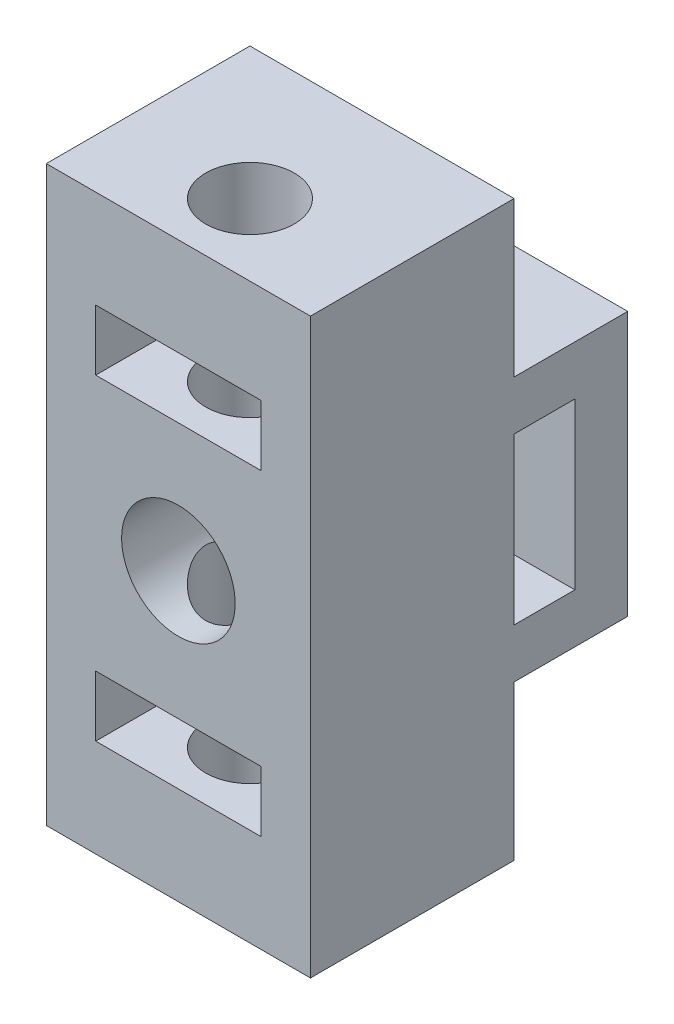
SolidWorks part; units mm, degrees
ref_plane "Front Plane" through (0, 0, 0) normal (0, 0, 1) x (1, 0, 0)
ref_plane "Top Plane" through (0, 0, 0) normal (0, 1, 0) x (1, 0, 0)
ref_plane "Right Plane" through (0, 0, 0) normal (1, 0, 0) x (0, 0, -1)
sketch "Sketch1" plane through (0, 0, 0) normal (0, 1, 0) x (1, 0, 0)
  line L1 (-5, -5) -> (5, -5)
  line L2 (-5, -5) -> (-5, 5)
  line L3 (-5, 5) -> (5, 5)
  line L4 (5, -5) -> (5, 5)
  line L5 (-5, -5) -> (5, 5) construction
  line L6 (-5, 5) -> (5, -5) construction
  point P0 (0, 0)
  dimension "D1" = 10
  dimension "D2" = 10
extrude "Boss-Extrude1" add sketch "Sketch1" along normal blind 5
sketch "Sketch2" plane through (0, 5, 0) normal (0, 1, 0) x (1, 0, 0)
  circle A0 centre (0, 0) radius 1.675
  dimension "D1" = 3.35
extrude "Cut-Extrude1" cut sketch "Sketch2" against normal through all both and the other way through all
sketch "Sketch3" plane through (0, 5, 0) normal (0, 1, 0) x (1, 0, 0)
  line L0 (-3.1292, 0) -> (-3.1292, -5)
  line L1 (3.1292, 0) -> (1.5646, 2.71)
  line L2 (1.5646, 2.71) -> (-1.5646, 2.71)
  line L3 (-1.5646, 2.71) -> (-3.1292, 0)
  line L4 (-3.1292, 0) -> (-1.5646, -2.71)
  line L5 (-1.5646, -2.71) -> (1.5646, -2.71)
  line L6 (1.5646, -2.71) -> (3.1292, 0)
  line L7 (-5, -5) -> (5, -5) construction
  line L8 (-3.1292, -5) -> (3.1292, -5)
  line L9 (3.1292, -5) -> (3.1292, 0)
  circle A0 centre (0, 0) radius 2.71 construction
  circle M7 centre (0, 0) radius 1.675
  line M11 (-5, -5) -> (5, -5)
  dimension "D1" = 5.42
extrude "Cut-Extrude3" cut sketch "Sketch3" against normal blind 2.3 contours L5 L6 L1 L2 L3 L4 M7 | L9 L6 L5 L4 L0 M11
sketch "Sketch4" plane through (0, 5, 0) normal (0, 1, 0) x (1, 0, 0)
  line L1 (-5, -5) -> (5, -5)
  line L2 (-5, -5) -> (-5, 5)
  line L3 (-5, 5) -> (5, 5)
  line L4 (5, -5) -> (5, 5)
extrude "Boss-Extrude2" add sketch "Sketch4" along normal blind 2.7
sketch "Sketch6" plane through (0, 7.7, 0) normal (0, 1, 0) x (1, 0, 0)
  line L1 (-5, -5) -> (5, -5)
  line L2 (-5, -5) -> (-5, 5)
  line L3 (-5, 5) -> (5, 5)
  line L4 (5, -5) -> (5, 5)
  line L5 (-5, -5) -> (5, 5) construction
  line L6 (-5, 5) -> (5, -5) construction
  point P0 (0, 0)
extrude "Boss-Extrude3" add sketch "Sketch6" along normal blind 7
sketch "Sketch9" plane through (0, 0, -5) normal (0, 0, -1) x (-1, 0, 0)
  line L0 (5, 14.7) -> (5, 0) construction
  line L1 (-5, 0) -> (5, 0)
  line L2 (-5, 0) -> (-5, 7.7)
  line L3 (-5, 7.7) -> (5, 7.7)
  line L4 (5, 0) -> (5, 7.7)
  circle A0 centre (0, 9.85) radius 2.15
  dimension "D2" = 4.3
  dimension "D1" = 7.7
  dimension "D3" = 2.15
extrude "Cut-Extrude12" cut sketch "Sketch9" against normal through all contours A0
sketch "Sketch10" plane through (0, 5, 0) normal (0, -1, 0) x (1, 0, 0)
  line L0 (-5, 5) -> (5, -5) construction
  circle A0 centre (0, 0) radius 1.675
  dimension "D1" = 3.35
extrude "Cut-Extrude13" cut sketch "Sketch10" against normal through all
sketch "Sketch11" plane through (0, 14.7, 0) normal (0, 1, 0) x (1, 0, 0)
  line L0 (-5, -5) -> (5, 5) construction
  line L1 (3.1292, 0) -> (1.5646, 2.71)
  line L2 (1.5646, 2.71) -> (-1.5646, 2.71)
  line L3 (-1.5646, 2.71) -> (-3.1292, 0)
  line L4 (-3.1292, 0) -> (-1.5646, -2.71)
  line L5 (-1.5646, -2.71) -> (1.5646, -2.71)
  line L6 (1.5646, -2.71) -> (3.1292, 0)
  line L7 (-3.1292, 0) -> (-3.1292, -5)
  line L8 (-3.1292, -5) -> (3.1292, -5)
  line L9 (-5, -5) -> (5, -5) construction
  line L10 (3.1292, -5) -> (3.1292, 0)
  line L11 (-3.1292, -5) -> (-5, -5)
  line L12 (-5, -5) -> (-5, 5)
  line L13 (-5, 5) -> (5, 5)
  line L14 (5, 5) -> (5, -5)
  line L15 (5, -5) -> (3.1292, -5)
  circle A0 centre (0, 0) radius 2.71 construction
  line M4 (5, -5) -> (5, 5)
  line M5 (5, 5) -> (-5, 5)
  line M6 (-5, 5) -> (-5, -5)
  line M7 (-5, -5) -> (5, -5)
  dimension "D1" = 5.42
extrude "Boss-Extrude4" add sketch "Sketch11" along normal blind 2.3 contours L10 L7 L3 L2 L1 M7 M4 M5 M6
sketch "Sketch12" plane through (0, 17, 0) normal (0, 1, 0) x (1, 0, 0)
  line L0 (-5, 5) -> (5, -5) construction
  line L1 (-5, -5) -> (5, -5)
  line L2 (-5, -5) -> (-5, 5)
  line L3 (-5, 5) -> (5, 5)
  line L4 (5, -5) -> (5, 5)
  line L5 (-5, -5) -> (5, 5) construction
  line L6 (-5, 5) -> (5, -5) construction
  point P0 (0, 0)
extrude "Boss-Extrude5" add sketch "Sketch12" along normal blind 2.7
sketch "Sketch13" plane through (0, 19.7, 0) normal (0, 1, 0) x (1, 0, 0)
  line L0 (-5, 5) -> (5, -5) construction
  circle A0 centre (0, 0) radius 1.675
  dimension "D1" = 3.35
extrude "Cut-Extrude14" cut sketch "Sketch13" against normal blind 2.7
sketch "Sketch14" plane through (0, 0, -5) normal (0, 0, -1) x (-1, 0, 0)
  line L0 (0, 7.7) -> (0, 12) construction
  circle A0 centre (0, 9.85) radius 2.15 construction
  circle A1 centre (0, 9.85) radius 2.15
  dimension "D1" = 4.3
extrude "Boss-Extrude6" add sketch "Sketch14" against normal blind 0.76 separate body
sketch "Sketch16" plane through (0, 0, 5) normal (0, 0, 1) x (1, 0, 0)
  line L0 (0, 0) -> (0, 19.7) construction
  line L1 (-5, 19.7) -> (5, 19.7) construction
  line L3 (-5, 0) -> (5, 0)
  line L4 (-5, 0) -> (-5, 19.7)
  line L5 (-5, 19.7) -> (5, 19.7)
  line L6 (5, 0) -> (5, 19.7)
  line L7 (-5, 0) -> (5, 19.7) construction
  line L8 (-5, 19.7) -> (5, 0) construction
  point P5 (0, 9.85)
extrude "Cut-Extrude15" cut sketch "Sketch16" against normal blind 2.29
sketch "Sketch17" plane through (0, 0, 0) normal (0, -1, 0) x (-1, 0, 0)
  line L0 (5, 5) -> (-5, -5) construction
  line L1 (5, -2.71) -> (-5, -2.71)
  line L2 (-5, -2.71) -> (-5, 5)
  line L3 (-5, 5) -> (5, 5)
  line L4 (5, 5) -> (5, -2.71)
  circle A0 centre (0, 0) radius 1.675
extrude "Boss-Extrude7" add sketch "Sketch17" along normal blind 1
sketch "Sketch18" plane through (0, 19.7, 0) normal (0, 1, 0) x (1, 0, 0)
  line L0 (-5, 5) -> (5, 5)
  line L1 (5, 5) -> (5, -2.71)
  line L2 (5, -2.71) -> (-5, -2.71)
  line L3 (-5, -2.71) -> (-5, 5)
  circle A0 centre (0, 0) radius 1.675
extrude "Boss-Extrude9" add sketch "Sketch18" along normal blind 1 contours L3 L0 L1 L2
sketch "Sketch22" plane through (0, 0, -5) normal (0, 0, -1) x (-1, 0, 0)
  line L0 (0, 12.9792) -> (-5, 12.9792)
  line L1 (0, 6.7208) -> (2.71, 8.2854)
  line L2 (2.71, 8.2854) -> (2.71, 11.4146)
  line L3 (2.71, 11.4146) -> (0, 12.9792)
  line L4 (0, 12.9792) -> (-2.71, 11.4146)
  line L5 (-2.71, 11.4146) -> (-2.71, 8.2854)
  line L6 (-2.71, 8.2854) -> (0, 6.7208)
  line L7 (-5, 4.85) -> (5, 4.85)
  line L8 (-5, 4.85) -> (-5, 14.85)
  line L9 (-5, 14.85) -> (5, 14.85)
  line L10 (5, 4.85) -> (5, 14.85)
  line L11 (-5, 4.85) -> (5, 14.85) construction
  line L12 (-5, 14.85) -> (5, 4.85) construction
  line L13 (0, 6.7208) -> (-5, 6.7208)
  circle A0 centre (0, 9.85) radius 2.71 construction
  dimension "D1" = 5.42
  dimension "D2" = 10
  dimension "D3" = 10
extrude "Boss-Extrude13" add sketch "Sketch22" along normal blind 2.3 contours L1 L13 L8 L7 L10 L9 L0 L3 L2
sketch "Sketch23" plane through (0, 0, -7.3) normal (0, 0, -1) x (-1, 0, 0)
  line L0 (-5, 14.85) -> (5, 4.85) construction
  line L1 (5, 14.85) -> (-5, 4.85) construction
  line L3 (-5, 4.85) -> (5, 4.85)
  line L4 (-5, 4.85) -> (-5, 14.85)
  line L5 (-5, 14.85) -> (5, 14.85)
  line L6 (5, 4.85) -> (5, 14.85)
  line L7 (-5, 4.85) -> (5, 14.85) construction
  line L8 (-5, 14.85) -> (5, 4.85) construction
  circle A0 centre (0, 9.85) radius 1.675
  point P8 (0, 9.85)
  dimension "D1" = 3.35
extrude "Boss-Extrude15" add sketch "Sketch23" along normal blind 2
